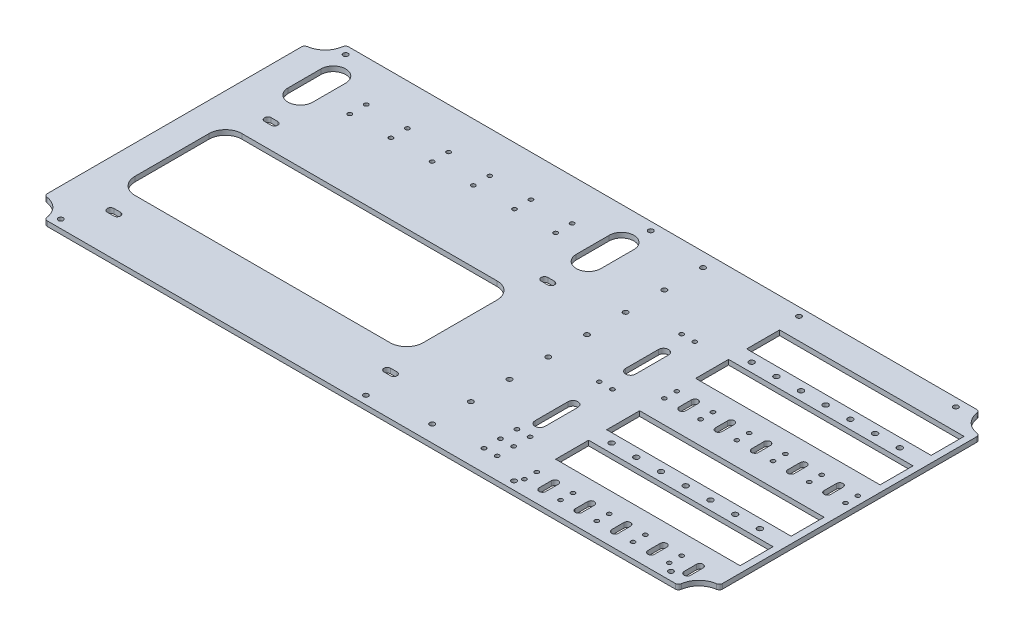
SolidWorks part; units mm, degrees
material "PBT General Purpose"
ref_plane "Front Plane" through (0, 0, 0) normal (0, 0, 1) x (1, 0, 0)
ref_plane "Top Plane" through (0, 0, 0) normal (0, 1, 0) x (1, 0, 0)
ref_plane "Right Plane" through (0, 0, 0) normal (1, 0, 0) x (0, 0, -1)
sketch "Sketch1" plane through (0, 0, 0) normal (0, 1, 0) x (1, 0, 0)
  line L0 (205, 183) -> (205, 0) construction
  line L2 (0, 14.3614) -> (0, 168.6386)
  line L3 (14.3614, 183) -> (395.6386, 183)
  line L4 (410, 14.3614) -> (410, 168.6386)
  line L5 (0, 91.5) -> (410, 91.5) construction
  line L6 (0, 183) -> (0, 170.5) construction
  line L7 (0, 183) -> (12.5, 183) construction
  line L8 (14.3614, 0) -> (395.6386, 0)
  arc A0 (12.3805, 181.2759) -> (1.7241, 170.6195) centre (0, 183) cw
  arc A1 (397.6195, 181.2759) -> (408.2759, 170.6195) centre (410, 183) ccw
  arc A2 (397.6195, 1.7241) -> (408.2759, 12.3805) centre (410, 0) cw
  arc A3 (12.3805, 1.7241) -> (1.7241, 12.3805) centre (0, 0) ccw
  arc A4 (14.3614, 183) -> (12.3805, 181.2759) centre (14.3614, 181) ccw
  arc A5 (1.7241, 170.6195) -> (0, 168.6386) centre (2, 168.6386) ccw
  arc A6 (0, 14.3614) -> (1.7241, 12.3805) centre (2, 14.3614) ccw
  arc A7 (12.3805, 1.7241) -> (14.3614, 0) centre (14.3614, 2) ccw
  arc A8 (395.6386, 0) -> (397.6195, 1.7241) centre (395.6386, 2) ccw
  arc A9 (408.2759, 12.3805) -> (410, 14.3614) centre (408, 14.3614) ccw
  arc A10 (408.2759, 170.6195) -> (410, 168.6386) centre (408, 168.6386) cw
  arc A11 (397.6195, 181.2759) -> (395.6386, 183) centre (395.6386, 181) ccw
  point P26 (0, 12.5)
  point P29 (12.5, 0)
  point P32 (397.5, 0)
  point P35 (410, 12.5)
  point P38 (410, 170.5)
  point P41 (397.5, 183)
  dimension "D3" = 91.5
  dimension "D5" = 12.5
  dimension "D6" = 2
  dimension "D1" = 183
  dimension "D2" = 410
  dimension "D4" = 205
extrude "Boss-Extrude1" add sketch "Sketch1" along normal blind 3
sketch "Sketch2" plane through (0, 3, 0) normal (0, 1, 0) x (1, 0, 0)
  line L0 (294, 145) -> (406, 145)
  line L5 (295, 163) -> (405, 163) construction
  line L6 (295, 163) -> (295, 116) construction
  line L27 (295, 116) -> (405, 116) construction
  line L28 (405, 163) -> (405, 116) construction
  line L29 (294, 165) -> (406, 165)
  line L30 (294, 165) -> (294, 145)
  line L31 (294, 114) -> (406, 114)
  line L32 (406, 165) -> (406, 145)
  line L33 (406, 134) -> (294, 134)
  line L34 (294, 134) -> (294, 114)
  line L35 (406, 134) -> (406, 114)
  line L36 (294, 80) -> (294, 60)
  line L37 (294, 80) -> (406, 80)
  line L38 (406, 80) -> (406, 60)
  line L39 (294, 60) -> (406, 60)
  line L40 (406, 49) -> (406, 29)
  line L41 (406, 49) -> (294, 49)
  line L42 (294, 49) -> (294, 29)
  line L43 (294, 29) -> (406, 29)
  line L45 (405, 139.5) -> (295, 139.5) construction
  circle A0 centre (302.5, 139.5) radius 1.6
  circle A1 centre (317.5, 139.5) radius 1.6
  circle A2 centre (332.5, 139.5) radius 1.6
  circle A3 centre (347.5, 139.5) radius 1.6
  circle A4 centre (362.5, 139.5) radius 1.6
  circle A5 centre (377.5, 139.5) radius 1.6
  circle A6 centre (392.5, 139.5) radius 1.6
  circle A7 centre (302.5, 54.5) radius 1.6
  circle A8 centre (317.5, 54.5) radius 1.6
  circle A9 centre (332.5, 54.5) radius 1.6
  circle A10 centre (347.5, 54.5) radius 1.6
  circle A11 centre (362.5, 54.5) radius 1.6
  circle A12 centre (377.5, 54.5) radius 1.6
  circle A13 centre (392.5, 54.5) radius 1.6
  dimension "D8" = 3.2
  dimension "D9" = 15
  dimension "D1" = 2
  dimension "D2" = 2
  dimension "D3" = 2
  dimension "D4" = 2
  dimension "D5" = 20
  dimension "D6" = 20
  dimension "D7" = 2
  dimension "D10" = 7
extrude "Cut-Extrude1" cut sketch "Sketch2" against normal up to next
sketch "Sketch3" plane through (0, 3, 0) normal (0, 1, 0) x (1, 0, 0)
  line L0 (236, 178) -> (236, 5) construction
  line L1 (240, 5) -> (240, 178) construction
  line L2 (236, 178) -> (236, 5) construction
  line L3 (240, 5) -> (240, 178) construction
  line L4 (238, 0) -> (238, 183) construction
  line L5 (14.3614, 0) -> (395.6386, 0) construction
  line L6 (395.6386, 183) -> (14.3614, 183) construction
  circle A0 centre (238, 10) radius 1.5
  circle A1 centre (238, 33.5) radius 1.5
  circle A2 centre (238, 57) radius 1.5
  circle A3 centre (238, 80.5) radius 1.5
  circle A4 centre (238, 104) radius 1.5
  circle A5 centre (238, 127.5) radius 1.5
  circle A6 centre (238, 151) radius 1.5
  circle A7 centre (238, 174.5) radius 1.5
  dimension "D2" = 3
  dimension "D3" = 10
  dimension "D1" = 2
extrude "Cut-Extrude2" cut sketch "Sketch3" against normal up to next
sketch "Sketch4" plane through (0, 3, 0) normal (0, 1, 0) x (1, 0, 0)
  line L0 (25, 143) -> (25, 163) construction
  line L1 (17.5, 143) -> (17.5, 163)
  line L2 (32.5, 143) -> (32.5, 163)
  line L3 (395.6386, 183) -> (14.3614, 183) construction
  line L4 (0, 168.6386) -> (0, 14.3614) construction
  line L5 (25, 153) -> (200, 153) construction
  line L6 (200, 143) -> (200, 163) construction
  line L7 (192.5, 143) -> (192.5, 163)
  line L8 (207.5, 143) -> (207.5, 163)
  line L9 (25, 158) -> (200, 158) construction
  line L10 (50, 158) -> (75, 158) construction
  arc A0 (17.5, 143) -> (32.5, 143) centre (25, 143) ccw
  arc A1 (32.5, 163) -> (17.5, 163) centre (25, 163) ccw
  arc A2 (192.5, 143) -> (207.5, 143) centre (200, 143) ccw
  arc A3 (207.5, 163) -> (192.5, 163) centre (200, 163) ccw
  circle A4 centre (50, 158) radius 1.25
  circle A5 centre (75, 158) radius 1.25
  circle A6 centre (100, 158) radius 1.25
  circle A7 centre (125, 158) radius 1.25
  circle A8 centre (150, 158) radius 1.25
  circle A9 centre (175, 158) radius 1.25
  circle A10 centre (175, 148) radius 1.25
  circle A11 centre (150, 148) radius 1.25
  circle A12 centre (125, 148) radius 1.25
  circle A13 centre (100, 148) radius 1.25
  circle A14 centre (75, 148) radius 1.25
  circle A15 centre (50, 148) radius 1.25
  point P2 (25, 153)
  point P15 (200, 153)
  dimension "D7" = 5
  dimension "D9" = 2.5
  dimension "D1" = 15
  dimension "D2" = 20
  dimension "D3" = 20
  dimension "D4" = 25
  dimension "D5" = 175
  dimension "D6" = 15
  dimension "D8" = 20
  dimension "D10" = 25
  dimension "D11" = 25
  dimension "D12" = 6
extrude "Cut-Extrude3" cut sketch "Sketch4" against normal up to next
sketch "Sketch8" plane through (0, 3, 0) normal (0, 1, 0) x (1, 0, 0)
  line L1 (405, 94) -> (295, 94) construction
  line L2 (294, 114) -> (406, 114) construction
  line L3 (410, 14.3614) -> (410, 168.6386) construction
  line L4 (405, 94) -> (383, 94) construction
  line L5 (405, 94) -> (405, 101.5) construction
  line L6 (405, 9) -> (295, 9) construction
  line L7 (405, 9) -> (383, 9) construction
  line L8 (405, 9) -> (405, 16.5) construction
  line L9 (405, 94) -> (405, 9) construction
  line L10 (394, 101.5) -> (394, 94) construction
  line L11 (396, 101.5) -> (396, 94)
  line L12 (392, 101.5) -> (392, 94)
  line L13 (372, 101.5) -> (372, 94) construction
  line L14 (374, 101.5) -> (374, 94)
  line L15 (370, 101.5) -> (370, 94)
  line L16 (350, 101.5) -> (350, 94) construction
  line L17 (352, 101.5) -> (352, 94)
  line L18 (348, 101.5) -> (348, 94)
  line L19 (328, 101.5) -> (328, 94) construction
  line L20 (330, 101.5) -> (330, 94)
  line L21 (326, 101.5) -> (326, 94)
  line L22 (306, 101.5) -> (306, 94) construction
  line L23 (308, 101.5) -> (308, 94)
  line L24 (304, 101.5) -> (304, 94)
  line L25 (394, 101.5) -> (372, 101.5) construction
  line L27 (394, 16.5) -> (394, 9) construction
  line L28 (396, 16.5) -> (396, 9)
  line L29 (392, 16.5) -> (392, 9)
  line L30 (372, 16.5) -> (372, 9) construction
  line L31 (374, 16.5) -> (374, 9)
  line L32 (370, 16.5) -> (370, 9)
  line L33 (350, 16.5) -> (350, 9) construction
  line L34 (352, 16.5) -> (352, 9)
  line L35 (348, 16.5) -> (348, 9)
  line L36 (328, 16.5) -> (328, 9) construction
  line L37 (330, 16.5) -> (330, 9)
  line L38 (326, 16.5) -> (326, 9)
  line L39 (306, 16.5) -> (306, 9) construction
  line L40 (308, 16.5) -> (308, 9)
  line L41 (304, 16.5) -> (304, 9)
  line L42 (394, 101.5) -> (394, 16.5) construction
  circle A0 centre (405, 94) radius 1.25
  circle A1 centre (383, 94) radius 1.25
  circle A2 centre (361, 94) radius 1.25
  circle A3 centre (339, 94) radius 1.25
  circle A4 centre (317, 94) radius 1.25
  circle A5 centre (295, 94) radius 1.25
  circle A6 centre (405, 101.5) radius 1.25
  circle A7 centre (383, 101.5) radius 1.25
  circle A8 centre (361, 101.5) radius 1.25
  circle A9 centre (339, 101.5) radius 1.25
  circle A10 centre (317, 101.5) radius 1.25
  circle A11 centre (295, 101.5) radius 1.25
  circle A13 centre (383, 9) radius 1.25
  circle A14 centre (361, 9) radius 1.25
  circle A15 centre (339, 9) radius 1.25
  circle A16 centre (317, 9) radius 1.25
  circle A17 centre (295, 9) radius 1.25
  circle A19 centre (383, 16.5) radius 1.25
  circle A20 centre (361, 16.5) radius 1.25
  circle A21 centre (339, 16.5) radius 1.25
  circle A22 centre (317, 16.5) radius 1.25
  circle A23 centre (295, 16.5) radius 1.25
  circle A24 centre (405, 9) radius 1.25 [skipped]
  circle A25 centre (405, 16.5) radius 1.25 [skipped]
  arc A26 (396, 101.5) -> (392, 101.5) centre (394, 101.5) ccw
  arc A27 (392, 94) -> (396, 94) centre (394, 94) ccw
  arc A28 (374, 101.5) -> (370, 101.5) centre (372, 101.5) ccw
  arc A29 (370, 94) -> (374, 94) centre (372, 94) ccw
  arc A30 (352, 101.5) -> (348, 101.5) centre (350, 101.5) ccw
  arc A31 (348, 94) -> (352, 94) centre (350, 94) ccw
  arc A32 (330, 101.5) -> (326, 101.5) centre (328, 101.5) ccw
  arc A33 (326, 94) -> (330, 94) centre (328, 94) ccw
  arc A34 (308, 101.5) -> (304, 101.5) centre (306, 101.5) ccw
  arc A35 (304, 94) -> (308, 94) centre (306, 94) ccw
  arc A36 (396, 16.5) -> (392, 16.5) centre (394, 16.5) ccw
  arc A37 (392, 9) -> (396, 9) centre (394, 9) ccw
  arc A38 (374, 16.5) -> (370, 16.5) centre (372, 16.5) ccw
  arc A39 (370, 9) -> (374, 9) centre (372, 9) ccw
  arc A40 (352, 16.5) -> (348, 16.5) centre (350, 16.5) ccw
  arc A41 (348, 9) -> (352, 9) centre (350, 9) ccw
  arc A42 (330, 16.5) -> (326, 16.5) centre (328, 16.5) ccw
  arc A43 (326, 9) -> (330, 9) centre (328, 9) ccw
  arc A44 (308, 16.5) -> (304, 16.5) centre (306, 16.5) ccw
  arc A45 (304, 9) -> (308, 9) centre (306, 9) ccw
  point P8 (394, 97.75)
  point P72 (372, 97.75)
  point P80 (350, 97.75)
  point P87 (328, 97.75)
  point P94 (306, 97.75)
  point P105 (394, 12.75)
  point P112 (372, 12.75)
  point P119 (350, 12.75)
  point P126 (328, 12.75)
  point P133 (306, 12.75)
  dimension "D4" = 2.5
  dimension "D1" = 20
  dimension "D2" = 5
  dimension "D3" = 110
  dimension "D5" = 22
  dimension "D7" = 7.5
  dimension "D8" = 85
  dimension "D10" = 7.5
  dimension "D11" = 11
  dimension "D12" = 4
  dimension "D14" = 22
  dimension "D16" = 85
  dimension "D6" = 6
  dimension "D9" = 2
  dimension "D13" = 5
  dimension "D15" = 2
extrude "Cut-Extrude4" cut sketch "Sketch8" against normal up to next (3 mm away)
sketch "Sketch9" plane through (0, 3, 0) normal (0, 1, 0) x (1, 0, 0)
  line L0 (255.5, 183) -> (255.5, 0) construction
  line L1 (255.5, 183) -> (255.5, 0) construction
  line L2 (270.5, 183) -> (270.5, 0) construction
  line L3 (395.6386, 183) -> (14.3614, 183) construction
  line L4 (14.3614, 0) -> (395.6386, 0) construction
  line L5 (270.5, 118) -> (270.5, 98) construction
  line L6 (273.5, 118) -> (273.5, 98)
  line L7 (267.5, 118) -> (267.5, 98)
  line L8 (270.5, 63) -> (270.5, 43) construction
  line L9 (273.5, 63) -> (273.5, 43)
  line L10 (267.5, 63) -> (267.5, 43)
  line L11 (270.5, 118) -> (270.5, 63) construction
  line L13 (274.5, 133) -> (274.5, 0) construction
  line L14 (274.5, 133) -> (278.9721, 124.0557) construction
  line L15 (266.5, 133) -> (262.0279, 124.0557) construction
  line L16 (266.5, 133) -> (266.5, 0) construction
  arc A0 (273.5, 118) -> (267.5, 118) centre (270.5, 118) ccw
  arc A1 (267.5, 98) -> (273.5, 98) centre (270.5, 98) ccw
  arc A2 (273.5, 63) -> (267.5, 63) centre (270.5, 63) ccw
  arc A3 (267.5, 43) -> (273.5, 43) centre (270.5, 43) ccw
  circle A4 centre (274.5, 133) radius 1.25
  circle A9 centre (274.5, 83) radius 1.25
  circle A14 centre (274.5, 33) radius 1.25
  circle A15 centre (274.5, 23) radius 1.25
  circle A16 centre (274.5, 13) radius 1.25
  circle A17 centre (274.5, 63) radius 1.25 [skipped]
  circle A18 centre (274.5, 53) radius 1.25 [skipped]
  circle A19 centre (274.5, 43) radius 1.25 [skipped]
  circle A20 centre (274.5, 93) radius 1.25 [skipped]
  circle A21 centre (274.5, 103) radius 1.25 [skipped]
  circle A22 centre (274.5, 113) radius 1.25 [skipped]
  circle A23 centre (274.5, 123) radius 1.25 [skipped]
  circle A24 centre (266.5, 33) radius 1.25
  circle A25 centre (266.5, 23) radius 1.25
  circle A26 centre (266.5, 13) radius 1.25
  circle A28 centre (266.5, 83) radius 1.25
  circle A29 centre (266.5, 133) radius 1.25
  circle A30 centre (274.5, 73) radius 1.25 [skipped]
  point P10 (270.5, 108)
  point P18 (270.5, 53)
  dimension "D7" = 2.5
  dimension "D1" = 15
  dimension "D2" = 20
  dimension "D3" = 6
  dimension "D4" = 65
  dimension "D6" = 55
  dimension "D8" = 4
  dimension "D9" = 50
  dimension "D10" = 13
  dimension "D11" = 10
  dimension "D5" = 2
extrude "Cut-Extrude5" cut sketch "Sketch9" against normal up to next
sketch "Sketch10" plane through (0, 3, 0) normal (0, 1, 0) x (1, 0, 0)
  line L0 (17.5, 178) -> (388, 178) construction
  line L1 (388, 178) -> (388, 5) construction
  line L2 (388, 5) -> (17.5, 5) construction
  line L3 (17.5, 5) -> (17.5, 178) construction
  line L4 (395.6386, 183) -> (14.3614, 183) construction
  line L5 (14.3614, 0) -> (395.6386, 0) construction
  line L6 (0, 168.6386) -> (0, 14.3614) construction
  line L7 (410, 14.3614) -> (410, 168.6386) construction
  line L8 (202.75, 178) -> (292.75, 178) construction
  circle A0 centre (17.5, 178) radius 1.5
  circle A1 centre (388, 178) radius 1.5
  circle A2 centre (388, 5) radius 1.5
  circle A3 centre (17.5, 5) radius 1.5
  circle A4 centre (202.75, 178) radius 1.5
  circle A5 centre (202.75, 5) radius 1.5
  circle A6 centre (292.75, 178) radius 1.5
  circle A7 centre (292.75, 5) radius 1.5
  dimension "D5" = 3
  dimension "D8" = 3
  dimension "D1" = 5
  dimension "D2" = 5
  dimension "D3" = 17.5
  dimension "D4" = 22
  dimension "D7" = 90
  dimension "D6" = 2
extrude "Cut-Extrude6" cut sketch "Sketch10" against normal up to next
sketch "Sketch11" plane through (0, 0, 0) normal (0, -1, 0) x (1, 0, 0)
  line L0 (32, -22.75) -> (28, -22.75) construction
  line L1 (28, -26.75) -> (32, -26.75) construction
  line L2 (196, -26.75) -> (200, -26.75) construction
  line L3 (200, -22.75) -> (196, -22.75) construction
  line L4 (196, -122.25) -> (200, -122.25) construction
  line L5 (200, -118.25) -> (196, -118.25) construction
  line L6 (28, -122.25) -> (32, -122.25) construction
  line L7 (32, -118.25) -> (28, -118.25) construction
  line L8 (32, -22.75) -> (28, -22.75)
  line L9 (28, -26.75) -> (32, -26.75)
  line L10 (196, -26.75) -> (200, -26.75)
  line L11 (200, -22.75) -> (196, -22.75)
  line L12 (196, -122.25) -> (200, -122.25)
  line L13 (200, -118.25) -> (196, -118.25)
  line L14 (28, -122.25) -> (32, -122.25)
  line L15 (32, -118.25) -> (28, -118.25)
  arc A0 (28, -22.75) -> (28, -26.75) centre (28, -24.75) ccw construction
  arc A1 (32, -26.75) -> (32, -22.75) centre (32, -24.75) ccw construction
  arc A2 (196, -22.75) -> (196, -26.75) centre (196, -24.75) ccw construction
  arc A3 (200, -26.75) -> (200, -22.75) centre (200, -24.75) ccw construction
  arc A4 (196, -118.25) -> (196, -122.25) centre (196, -120.25) ccw construction
  arc A5 (200, -122.25) -> (200, -118.25) centre (200, -120.25) ccw construction
  arc A6 (28, -118.25) -> (28, -122.25) centre (28, -120.25) ccw construction
  arc A7 (32, -122.25) -> (32, -118.25) centre (32, -120.25) ccw construction
  arc A8 (28, -22.75) -> (28, -26.75) centre (28, -24.75) ccw
  arc A9 (32, -26.75) -> (32, -22.75) centre (32, -24.75) ccw
  arc A10 (196, -22.75) -> (196, -26.75) centre (196, -24.75) ccw
  arc A11 (200, -26.75) -> (200, -22.75) centre (200, -24.75) ccw
  arc A12 (196, -118.25) -> (196, -122.25) centre (196, -120.25) ccw
  arc A13 (200, -122.25) -> (200, -118.25) centre (200, -120.25) ccw
  arc A14 (28, -118.25) -> (28, -122.25) centre (28, -120.25) ccw
  arc A15 (32, -122.25) -> (32, -118.25) centre (32, -120.25) ccw
extrude "Cut-Extrude7" cut sketch "Sketch11" against normal up to next
sketch "Sketch12" plane through (0, 3, 0) normal (0, 1, 0) x (1, 0, 0)
  line L0 (207.5, 72.5) -> (2.5, 72.5) construction
  line L1 (27.5, 105) -> (182.5, 105)
  line L2 (17.5, 95) -> (17.5, 50)
  line L3 (27.5, 40) -> (182.5, 40)
  line L4 (192.5, 95) -> (192.5, 50)
  line L5 (207.5, 15) -> (207.5, 130) construction
  line L6 (2.5, 15) -> (2.5, 130) construction
  line L7 (2.5, 130) -> (207.5, 130) construction
  arc A0 (17.5, 50) -> (27.5, 40) centre (27.5, 50) ccw
  arc A1 (182.5, 40) -> (192.5, 50) centre (182.5, 50) ccw
  arc A2 (192.5, 95) -> (182.5, 105) centre (182.5, 95) ccw
  arc A3 (27.5, 105) -> (17.5, 95) centre (27.5, 95) ccw
  point P10 (17.5, 72.5)
  dimension "D4" = 10
  dimension "D1" = 15
  dimension "D2" = 15
  dimension "D3" = 25
extrude "Cut-Extrude8" cut sketch "Sketch12" against normal up to next
